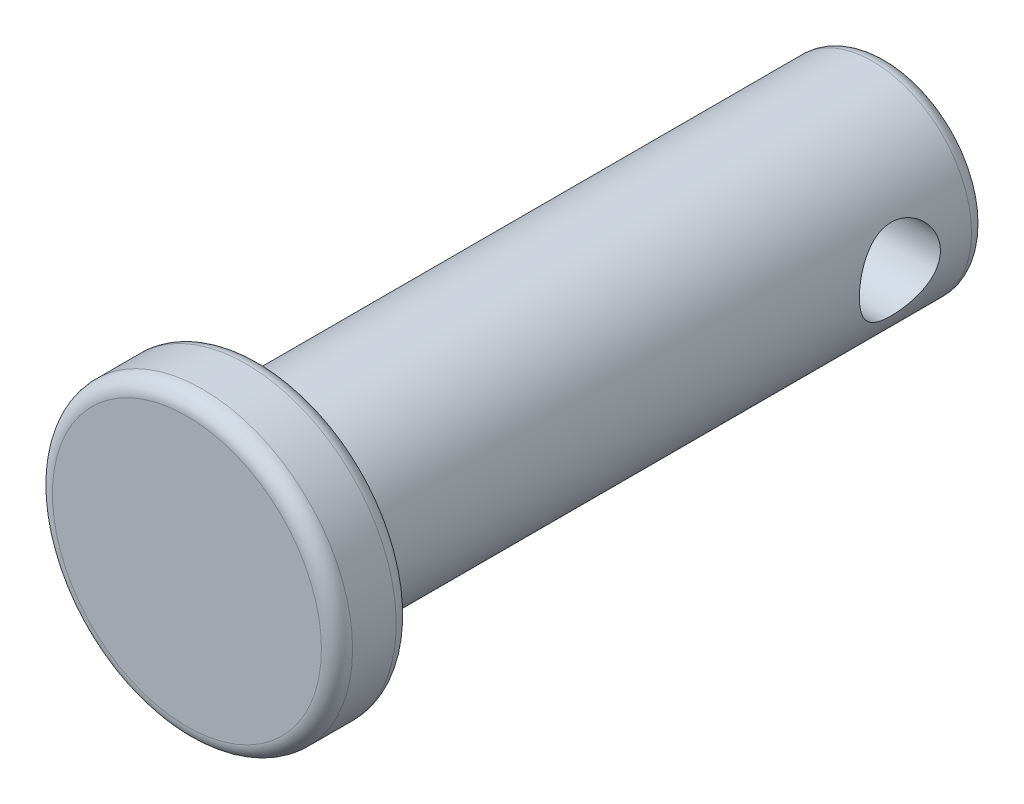
SolidWorks part; units mm, degrees
ref_plane "Front Plane" through (0, 0, 0) normal (1, 0, 0) x (0, 1, 0)
ref_plane "Top Plane" through (0, 0, 0) normal (0, 0, 1) x (0, 1, 0)
ref_plane "Right Plane" through (0, 0, 0) normal (0, 1, 0) x (-1, 0, 0)
sketch "Sketch1" plane through (0, 0, 0) normal (1, 0, 0) x (0, 1, 0)
  line L0 (0, 0) -> (4.815, 0)
  line L1 (4.815, 0) -> (4.815, -2.4)
  line L2 (4.815, -2.4) -> (3.175, -2.4)
  line L3 (3.175, -2.4) -> (3.175, -53.2)
  line L4 (3.175, -53.2) -> (0, -53.2)
  line L5 (0, -53.2) -> (0, 0)
  line L6 (0, -335.5768) -> (0, 16305.0472) construction
  dimension "D1" = 6.35
  dimension "D2" = 50.8
  dimension "D3" = 1.64
  dimension "D4" = 2.4
revolve "Revolve1" add sketch "Sketch1" angle 360 about L6
sketch "Sketch2" plane through (0, 0, 0) normal (1, 0, 0) x (0, 1, 0)
  line L0 (0, -47.7) -> (0, -42.1) construction
  line L1 (0, -42.1) -> (0, -36.5) construction
  line L2 (0, -36.5) -> (0, -30.9) construction
  line L3 (0, -30.9) -> (0, -25.3) construction
  line L4 (0, -25.3) -> (0, -19.7) construction
  line L5 (0, -47.7) -> (0, -49) construction
  line L6 (-3.175, -53.2) -> (3.175, -53.2) construction
  circle A0 centre (0, -47.7) radius 1.3
  circle A1 centre (0, -42.1) radius 1.3
  circle A3 centre (0, -25.3) radius 1.3
  circle A4 centre (0, -30.9) radius 1.3
  circle A6 centre (0, -36.5) radius 1.3
  circle A7 centre (0, -19.7) radius 1.3
  point P11 (0, -46.4)
  point P14 (0, -43.4)
  dimension "D1" = 2.6
  dimension "D2" = 4.2
  dimension "D3" = 3
extrude "Cut-Extrude1" cut sketch "Sketch2" against normal through all both and the other way through all
fillet "f7f" radius 0.5 2 edges at (-4.815, 0, -2.4) (-4.815, 0, 0)
sketch "Sketch3" plane through (0, 0, 0) normal (1, 0, 0) x (0, 1, 0)
  line L1 (-3.175, -22.5) -> (3.175, -22.5)
  line L2 (-3.175, -22.5) -> (-3.175, -53.2)
  line L3 (-3.175, -53.2) -> (3.175, -53.2)
  line L4 (3.175, -22.5) -> (3.175, -53.2)
  line L5 (-3.175, -2.4) -> (-3.175, -53.2) construction
  line L6 (0, -21) -> (0, -22.5) construction
  line L7 (0, -22.5) -> (0, -24) construction
  circle A0 centre (0, -19.7) radius 1.3 construction
  circle A1 centre (0, -25.3) radius 1.3 construction
extrude "Cut-Extrude2" cut sketch "Sketch3" against normal through all both and the other way through all
fillet "Fillet1" radius 0.5 1 edges at (3.175, 0, -22.5)
